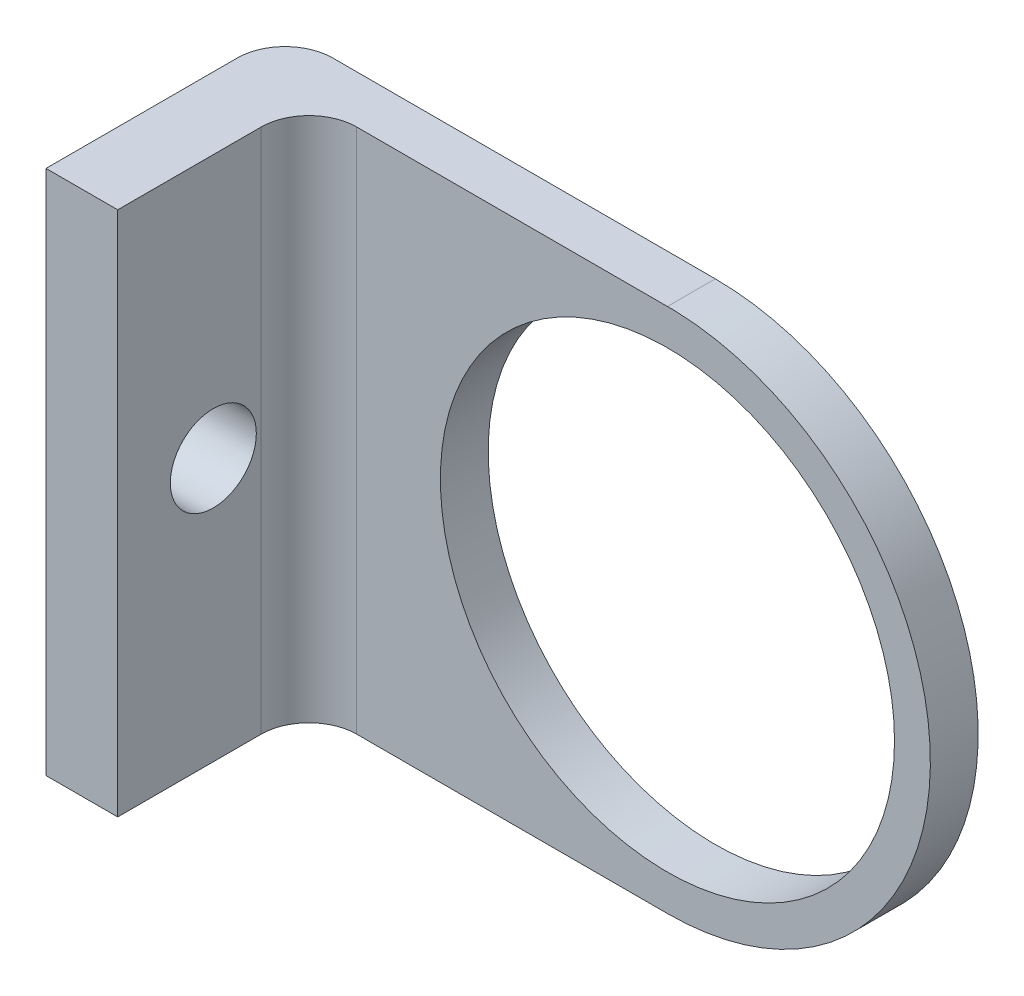
SolidWorks part; units mm, degrees
ref_plane "Front Plane" through (0, 0, 0) normal (1, 0, 0) x (0, 1, 0)
ref_plane "Top Plane" through (0, 0, 0) normal (0, 0, 1) x (0, 1, 0)
ref_plane "Right Plane" through (0, 0, 0) normal (0, 1, 0) x (-1, 0, 0)
sketch "Sketch1" plane through (0, 0, 0) normal (0, 0, 1) x (0, 1, 0)
  line L0 (-11, 0) -> (-11, 18)
  line L1 (-11, 18) -> (11, 18)
  line L2 (0, 18) -> (0, 11)
  line L3 (0, 18) -> (0, -20.619) construction
  line L4 (-11, 0) -> (-9.5, 0)
  line L5 (-9.5, 0) -> (9.5, 0)
  line L6 (0, 0) -> (0, 9.5)
  line L7 (11, 0) -> (9.5, 0)
  line L8 (11, 0) -> (11, 18)
  circle A0 centre (0, 0) radius 9.5
  circle A1 centre (0, 0) radius 11
  dimension "D1" = 19
  dimension "D2" = 22
  dimension "D3" = 18
extrude "10 mm extrude" add sketch "Sketch1" along normal blind 10 contours A1 L2 L1 L0 | A1 L8 L1 L2 | L3 A1 L4 A0 | A1 L3 A0 L7 | A0 L3 A1 L7 | L3 A0 L4 A1
sketch "Sketch2" plane through (0, 0, 10) normal (0, 0, 1) x (0, -1, 0)
  line L0 (-11, -18) -> (11, -18) construction
  line L1 (0, -18) -> (0, 11) construction
  line L2 (0, -11) -> (-11, -11)
  line L3 (-11, 0) -> (-11, -18) construction
  line L4 (-11, -11) -> (-10.9932, 0.3866)
  line L5 (0, -11) -> (11, -11)
  line L6 (11, 0) -> (11, -18) construction
  line L7 (11, -11) -> (11, 0)
  line L8 (0, -18) -> (0, -15)
  line L9 (-11, -15) -> (11, -15)
  arc A0 (11, 0) -> (-11, 0) centre (0, 0) ccw construction
  circle A1 centre (0, 0) radius 11
  arc M2 (11, 0) -> (-11, 0) centre (0, 0) ccw
  line M3 (-11, 0) -> (-11, -18)
  line M5 (11, -18) -> (11, 0)
  circle M6 centre (0, 0) radius 9.5
  dimension "D1" = 3
extrude "8 mm cut" cut sketch "Sketch2" against normal blind 8 contours A1 L4 L2 | A1 L5 M5 | L4 A1 M2 M6 | M6 | L9 L5 L2 M3 M5
sketch "Sketch4" plane through (-15, 0, 0) normal (1, 0, 0) x (0, 1, 0)
  line L0 (0, 10) -> (-0.0034, 2) construction
  line L1 (11, 10) -> (-11, 10) construction
  line L2 (10.9932, 2) -> (-11, 2) construction
  circle A0 centre (-0.0017, 6) radius 1.8
  dimension "D1" = 3.6
extrude "3.6D" cut sketch "Sketch4" against normal blind 8
fillet "R2 Filet" radius 2 2 edges at (-15, 0, 2) (-18, 0, 0)
